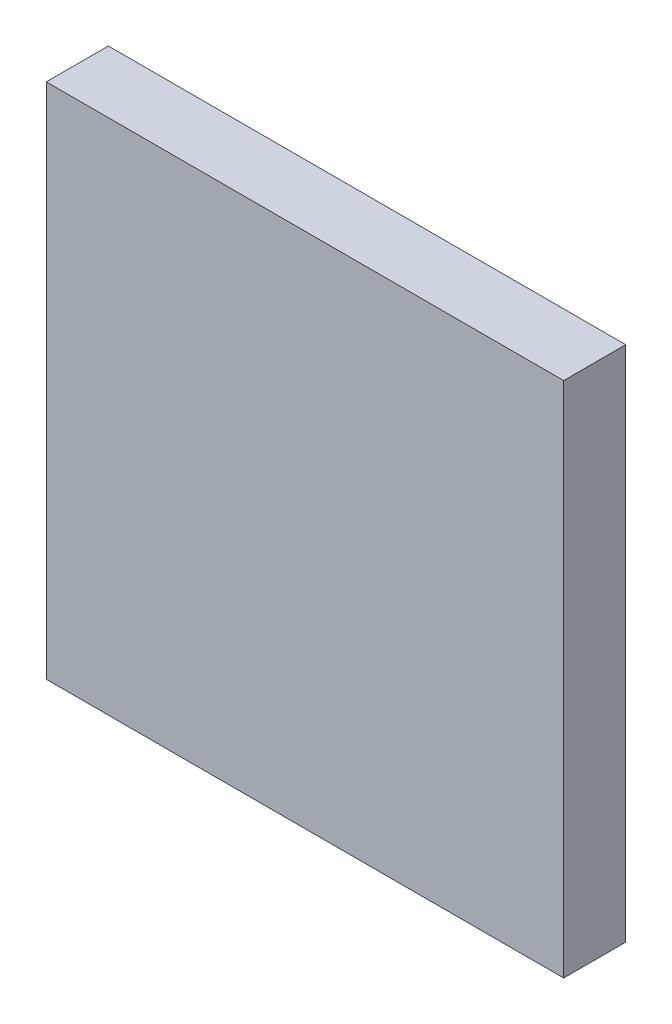
SolidWorks part; units mm, degrees
ref_plane "Front Plane" through (0, 0, 0) normal (0, 0, 1) x (1, 0, 0)
ref_plane "Top Plane" through (0, 0, 0) normal (0, 1, 0) x (1, 0, 0)
ref_plane "Right Plane" through (0, 0, 0) normal (1, 0, 0) x (0, 0, -1)
sketch "Sketch1" plane through (0, 0, 0) normal (0, 0, 1) x (1, 0, 0)
  line L1 (0, 0) -> (25, 0)
  line L2 (0, 0) -> (0, -25)
  line L3 (0, -25) -> (25, -25)
  line L4 (25, 0) -> (25, -25)
  dimension "D1" = 25
extrude "Boss-Extrude1" add sketch "Sketch1" along normal blind 3
